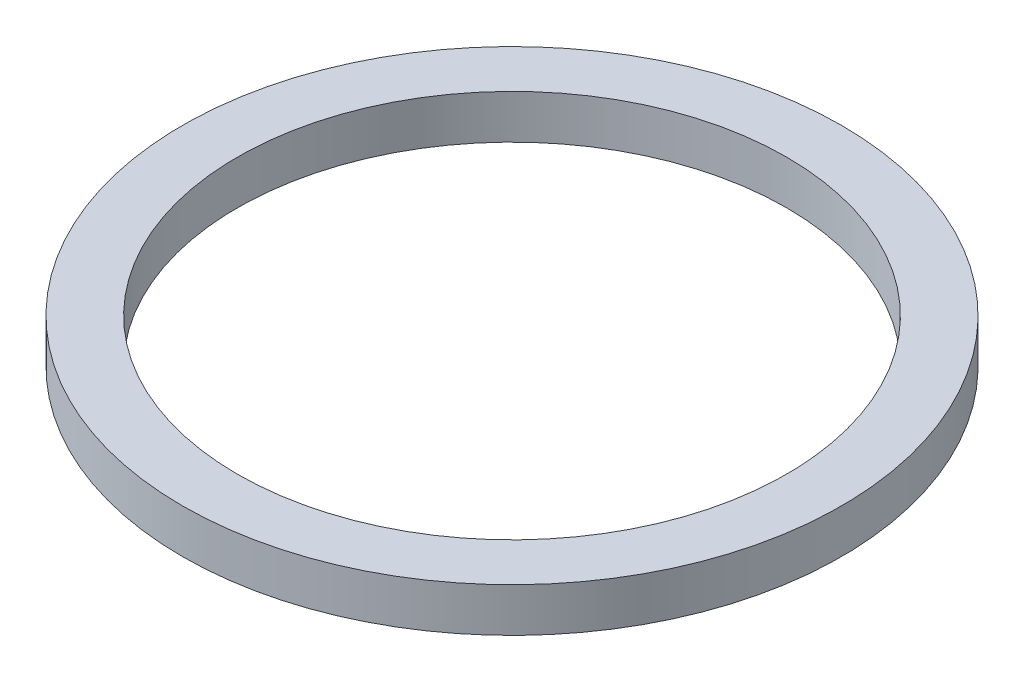
SolidWorks part; units mm, degrees
material "AISI 4130 Steel, normalized at 870C"
ref_plane "Front Plane" through (0, 0, 0) normal (0, 0, 1) x (1, 0, 0)
ref_plane "Top Plane" through (0, 0, 0) normal (0, 1, 0) x (1, 0, 0)
ref_plane "Right Plane" through (0, 0, 0) normal (1, 0, 0) x (0, 0, -1)
sketch "Sketch1" plane through (0, 0, 0) normal (0, 1, 0) x (1, 0, 0)
  circle A0 centre (0, 0) radius 15
  circle A1 centre (0, 0) radius 12.5
  dimension "D1" = 30
  dimension "D2" = 25
extrude "Boss-Extrude1" add sketch "Sketch1" along normal blind 2
